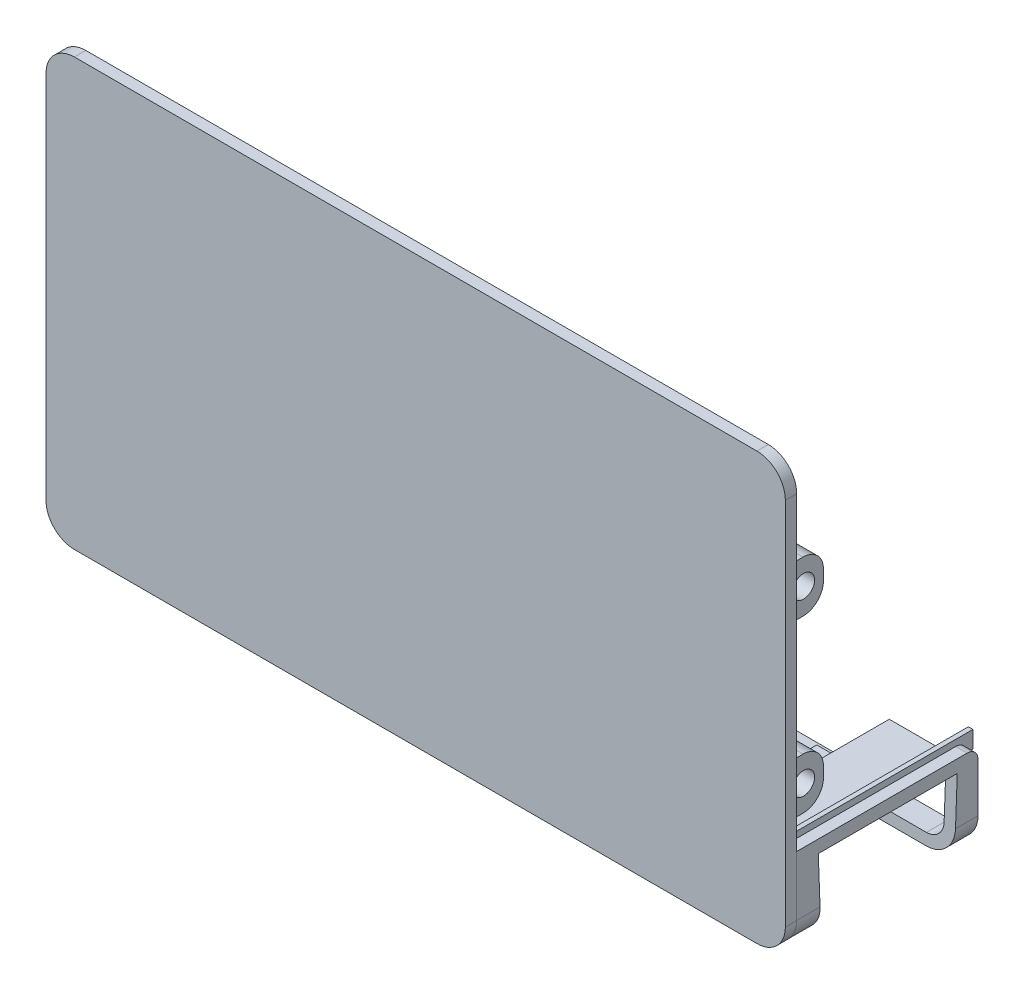
SolidWorks part; units mm, degrees
ref_plane "前视基准面" through (0, 0, 0) normal (0, 0, 1) x (1, 0, 0)
ref_plane "上视基准面" through (0, 0, 0) normal (0, 1, 0) x (1, 0, 0)
ref_plane "右视基准面" through (0, 0, 0) normal (1, 0, 0) x (0, 0, -1)
other "Configuration Table"
sketch "草图25" plane through (0, 0, 0) normal (0, 0, 1) x (1, 0, 0)
  line L0 (-60, -37.5) -> (60, -37.5)
  line L1 (65, -32.5) -> (65, 32.5)
  line L2 (60, 37.5) -> (-60, 37.5)
  line L3 (-65, 32.5) -> (-65, -32.5)
  arc A0 (60, -37.5) -> (65, -32.5) centre (60, -32.5) ccw
  arc A1 (65, 32.5) -> (60, 37.5) centre (60, 32.5) ccw
  arc A2 (-60, 37.5) -> (-65, 32.5) centre (-60, 32.5) ccw
  arc A3 (-65, -32.5) -> (-60, -37.5) centre (-60, -32.5) ccw
extrude "Flat_bottom_cover_T2" add sketch "草图25" along normal blind 2
sketch "草图26" plane through (0, 0, 0) normal (0, 0, 1) x (1, 0, 0)
  line L0 (-62.7, -19) -> (-56.3, -19)
  line L1 (-56.3, -19) -> (-56.3, -10)
  line L2 (-56.3, -10) -> (-62.7, -10)
  line L3 (-62.7, -10) -> (-62.7, -19)
  line L4 (-62.7, 11) -> (-56.3, 11)
  line L5 (-56.3, 11) -> (-56.3, 20)
  line L6 (-56.3, 20) -> (-62.7, 20)
  line L7 (-62.7, 20) -> (-62.7, 11)
extrude "Side_lock_ears_-1" add sketch "草图26" against normal blind 7
sketch "草图27" plane through (0, 0, 0) normal (0, 0, 1) x (1, 0, 0)
  line L0 (56.3, -19) -> (62.7, -19)
  line L1 (62.7, -19) -> (62.7, -10)
  line L2 (62.7, -10) -> (56.3, -10)
  line L3 (56.3, -10) -> (56.3, -19)
  line L4 (56.3, 11) -> (62.7, 11)
  line L5 (62.7, 11) -> (62.7, 20)
  line L6 (62.7, 20) -> (56.3, 20)
  line L7 (56.3, 20) -> (56.3, 11)
extrude "Side_lock_ears_1" add sketch "草图27" against normal blind 7
sketch "草图28" plane through (-62.7, 0, 0) normal (-1, 0, 0) x (0, 0, 1)
  circle A0 centre (-3.5, -14.5) radius 1.45
  circle A1 centre (-3.5, 15.5) radius 1.45
extrude "Screw_tip_relief_D2.9_-1" cut sketch "草图28" against normal blind 5.6
sketch "草图29" plane through (-62.7, 0, 0) normal (-1, 0, 0) x (0, 0, 1)
  circle A0 centre (-3.5, -14.5) radius 1.95
  circle A1 centre (-3.5, 15.5) radius 1.95
extrude "M2.5_heatset_D3.9_depth3.5_-1" cut sketch "草图29" against normal blind 3.5
sketch "草图30" plane through (62.7, 0, 0) normal (1, 0, 0) x (0, 0, -1)
  circle A0 centre (3.5, -14.5) radius 1.45
  circle A1 centre (3.5, 15.5) radius 1.45
extrude "Screw_tip_relief_D2.9_1" cut sketch "草图30" against normal blind 5.6
sketch "草图31" plane through (62.7, 0, 0) normal (1, 0, 0) x (0, 0, -1)
  circle A0 centre (3.5, -14.5) radius 1.95
  circle A1 centre (3.5, 15.5) radius 1.95
extrude "M2.5_heatset_D3.9_depth3.5_1" cut sketch "草图31" against normal blind 3.5
fillet "圆角1" radius 3.6 8 edges at (-59.5, -19, -7) (-59.5, -10, -7) (-59.5, 20, -7) (-59.5, 11, -7) (59.5, 20, -7) (59.5, 11, -7) (59.5, -10, -7) (59.5, -19, -7)
sketch "草图34" plane through (0, 0, 0) normal (0, 0, -1) x (-1, 0, 0)
  line L0 (59.9, -37.5) -> (59.9, -35.5)
  line L1 (60, -37.5) -> (-60, -37.5) construction
  line L2 (60, -35.5) -> (60, -38.0414) construction
  line L3 (-64.9748, -21.9) -> (-70.1323, -21.9) construction
  line L4 (-64.9748, -22) -> (-62.9748, -22)
  line L5 (-62.9748, -22) -> (-62.9748, -32.5)
  line L7 (-64.9748, -22) -> (-64.9748, -32.5)
  line L8 (-59.9748, -35.5) -> (59.9, -35.5)
  line L9 (59.9, -37.5) -> (-59.9748, -37.5)
  arc A0 (-62.9748, -32.5) -> (-59.9748, -35.5) centre (-59.9748, -32.5) ccw
  arc A1 (-64.9748, -32.5) -> (-59.9748, -37.5) centre (-59.9748, -32.5) ccw
  dimension "D1" = 2
  dimension "D2" = 0.1
  dimension "D4" = 0.1
  dimension "D3" = 2
extrude "凸台-拉伸2" add sketch "草图34" along normal blind 31.9
fillet "圆角2" radius 1.9 2 edges at (-59.9, -36.5, -31.9) (63.9748, -22, -31.9)
sketch "草图35" plane through (64.9748, 0, 0) normal (1, 0, 0) x (0, 0, -1)
  line L1 (28.2533, -24.2301) -> (3.8188, -24.2301)
  line L2 (28.2533, -24.2301) -> (27.6089, -41.4145)
  line L3 (27.6089, -41.4145) -> (4.4609, -41.4145)
  line L4 (3.8188, -24.2301) -> (4.4609, -41.4145)
extrude "切除-拉伸1" cut sketch "草图35" against normal blind 17
sketch "草图36" plane through (0, 0, 0) normal (0, 0, -1) x (-1, 0, 0)
  line L0 (-64.9748, -22) -> (-62.9748, -22) construction
  line L1 (-62.9748, -22) -> (-52.9748, -22)
  line L2 (-62.9748, -22) -> (-62.9748, -24.2301)
  line L3 (-62.9748, -24.2301) -> (-52.9748, -24.2301)
  line L4 (-52.9748, -22) -> (-52.9748, -24.2301)
  line L5 (-62.9748, -24.2301) -> (-64.9748, -24.2301) construction
  line L6 (58, -35.5) -> (-59.9748, -35.5) construction
  line L7 (-47.9725, -32.2834) -> (-40.2423, -32.2834)
  line L8 (-47.9725, -32.2834) -> (-47.9725, -35.5)
  line L9 (-47.9725, -35.5) -> (-40.2423, -35.5)
  line L10 (-40.2423, -32.2834) -> (-40.2423, -35.5)
  dimension "D1" = 10
extrude "凸台-拉伸3" add sketch "草图36" along normal blind 28.3
sketch "草图38" plane through (0, -32.2834, 0) normal (0, 1, 0) x (1, 0, 0)
  circle A0 centre (45.1498, 23.9901) radius 2
  circle A1 centre (45.165, 7.9909) radius 2
  dimension "D1" = 4
extrude "切除-拉伸2" cut sketch "草图38" against normal blind 3.4
sketch "草图39" plane through (0, 0, 0) normal (0, 0, -1) x (-1, 0, 0)
  line L0 (62.9, -32.5) -> (62.1, -32.5)
  line L1 (60, -35.4) -> (59.9, -35.4)
  line L2 (59.9, -35.4) -> (59.9, -35.5)
  line L3 (60, -34.6) -> (58, -34.6)
  line L4 (58, -34.6) -> (58, -35.5)
  line L5 (58, -37.5) -> (58, -35.5) construction
  line L6 (58, -35.5) -> (59.9, -35.5)
  line L7 (-62.9748, -23.9) -> (-64.9748, -23.9) construction
  line L8 (-62.9748, -23.9) -> (-62.1748, -23.9)
  line L9 (-62.9748, -23.9) -> (-62.9748, -20.9)
  line L10 (-62.9748, -20.9) -> (-62.1748, -20.9)
  line L11 (-62.1748, -23.9) -> (-62.1748, -20.9)
  line L12 (59.9, -35.5) -> (-40.2423, -35.5) construction
  arc A1 (60, -34.6) -> (62.1, -32.5) centre (60, -32.5) ccw
  arc A2 (60, -35.4) -> (62.9, -32.5) centre (60, -32.5) ccw
  arc A3 (60, -35.4) -> (62.9, -32.5) centre (60, -32.5) ccw
  dimension "D3" = 0.8
  dimension "D4" = 3
  dimension "D1" = 2.1
  dimension "D2" = 0.8
extrude "凸台-拉伸4" add sketch "草图39" along normal blind 33
sketch "草图40" plane through (0, -37.5, 0) normal (0, -1, 0) x (1, 0, 0)
  line L0 (59.9748, -31.9) -> (-58, -31.9) construction
  line L1 (64.9748, -31.9) -> (64.9748, -27.9432) construction
  circle A0 centre (21.9748, -27.4) radius 1
  circle A1 centre (17.9748, -27.4) radius 1
  circle A2 centre (13.9748, -27.4) radius 1
  circle A3 centre (9.9748, -27.4) radius 1
  circle A4 centre (5.9748, -27.4) radius 1
  circle A5 centre (1.9748, -27.4) radius 1
  circle A6 centre (-2.0252, -27.4) radius 1
  circle A7 centre (-6.0252, -27.4) radius 1
  circle A8 centre (-10.0252, -27.4) radius 1
  circle A9 centre (-14.0252, -27.4) radius 1
  circle A10 centre (-18.0252, -27.4) radius 1
  circle A11 centre (-22.0252, -27.4) radius 1
  circle A12 centre (-26.0252, -27.4) radius 1
  circle A13 centre (-30.0252, -27.4) radius 1
  circle A14 centre (-34.0252, -27.4) radius 1
  circle A15 centre (-38.0252, -27.4) radius 1
  circle A16 centre (-42.0252, -27.4) radius 1
  circle A17 centre (-46.0252, -27.4) radius 1
  circle A18 centre (-50.0252, -27.4) radius 1
  circle A19 centre (-54.0252, -27.4) radius 1
  circle A20 centre (17.9748, -23.4) radius 1
  circle A21 centre (13.9748, -23.4) radius 1
  circle A22 centre (9.9748, -23.4) radius 1
  circle A23 centre (5.9748, -23.4) radius 1
  circle A24 centre (1.9748, -23.4) radius 1
  circle A25 centre (-2.0252, -23.4) radius 1
  circle A26 centre (-6.0252, -23.4) radius 1
  circle A27 centre (-10.0252, -23.4) radius 1
  circle A28 centre (-14.0252, -23.4) radius 1
  circle A29 centre (-18.0252, -23.4) radius 1
  circle A30 centre (-22.0252, -23.4) radius 1
  circle A31 centre (-26.0252, -23.4) radius 1
  circle A32 centre (-30.0252, -23.4) radius 1
  circle A33 centre (-34.0252, -23.4) radius 1
  circle A34 centre (-38.0252, -23.4) radius 1
  circle A35 centre (-42.0252, -23.4) radius 1
  circle A36 centre (-46.0252, -23.4) radius 1
  circle A37 centre (-50.0252, -23.4) radius 1
  circle A38 centre (-54.0252, -23.4) radius 1
  circle A39 centre (17.9748, -19.4) radius 1
  circle A40 centre (13.9748, -19.4) radius 1
  circle A41 centre (9.9748, -19.4) radius 1
  circle A42 centre (5.9748, -19.4) radius 1
  circle A43 centre (1.9748, -19.4) radius 1
  circle A44 centre (-2.0252, -19.4) radius 1
  circle A45 centre (-6.0252, -19.4) radius 1
  circle A46 centre (-10.0252, -19.4) radius 1
  circle A47 centre (-14.0252, -19.4) radius 1
  circle A48 centre (-18.0252, -19.4) radius 1
  circle A49 centre (-22.0252, -19.4) radius 1
  circle A50 centre (-26.0252, -19.4) radius 1
  circle A51 centre (-30.0252, -19.4) radius 1
  circle A52 centre (-34.0252, -19.4) radius 1
  circle A53 centre (-38.0252, -19.4) radius 1
  circle A54 centre (-42.0252, -19.4) radius 1
  circle A55 centre (-46.0252, -19.4) radius 1
  circle A56 centre (-50.0252, -19.4) radius 1
  circle A57 centre (-54.0252, -19.4) radius 1
  circle A58 centre (17.9748, -15.4) radius 1
  circle A59 centre (13.9748, -15.4) radius 1
  circle A60 centre (9.9748, -15.4) radius 1
  circle A61 centre (5.9748, -15.4) radius 1
  circle A62 centre (1.9748, -15.4) radius 1
  circle A63 centre (-2.0252, -15.4) radius 1
  circle A64 centre (-6.0252, -15.4) radius 1
  circle A65 centre (-10.0252, -15.4) radius 1
  circle A66 centre (-14.0252, -15.4) radius 1
  circle A67 centre (-18.0252, -15.4) radius 1
  circle A68 centre (-22.0252, -15.4) radius 1
  circle A69 centre (-26.0252, -15.4) radius 1
  circle A70 centre (-30.0252, -15.4) radius 1
  circle A71 centre (-34.0252, -15.4) radius 1
  circle A72 centre (-38.0252, -15.4) radius 1
  circle A73 centre (-42.0252, -15.4) radius 1
  circle A74 centre (-46.0252, -15.4) radius 1
  circle A75 centre (-50.0252, -15.4) radius 1
  circle A76 centre (-54.0252, -15.4) radius 1
  circle A77 centre (17.9748, -11.4) radius 1
  circle A78 centre (13.9748, -11.4) radius 1
  circle A79 centre (9.9748, -11.4) radius 1
  circle A80 centre (5.9748, -11.4) radius 1
  circle A81 centre (1.9748, -11.4) radius 1
  circle A82 centre (-2.0252, -11.4) radius 1
  circle A83 centre (-6.0252, -11.4) radius 1
  circle A84 centre (-10.0252, -11.4) radius 1
  circle A85 centre (-14.0252, -11.4) radius 1
  circle A86 centre (-18.0252, -11.4) radius 1
  circle A87 centre (-22.0252, -11.4) radius 1
  circle A88 centre (-26.0252, -11.4) radius 1
  circle A89 centre (-30.0252, -11.4) radius 1
  circle A90 centre (-34.0252, -11.4) radius 1
  circle A91 centre (-38.0252, -11.4) radius 1
  circle A92 centre (-42.0252, -11.4) radius 1
  circle A93 centre (-46.0252, -11.4) radius 1
  circle A94 centre (-50.0252, -11.4) radius 1
  circle A95 centre (-54.0252, -11.4) radius 1
  circle A96 centre (21.9748, -23.4) radius 1
  circle A97 centre (21.9748, -19.4) radius 1
  circle A98 centre (21.9748, -15.4) radius 1
  circle A99 centre (21.9748, -11.4) radius 1
  dimension "D1" = 2
  dimension "D2" = 4.5
  dimension "D3" = 43
  dimension "D4" = 20
  dimension "D5" = 5
extrude "切除-拉伸3" cut sketch "草图40" against normal up to next (2 mm away)
ref_plane "基准面1" through (16.4748, 0, 0) normal (1, 0, 0) x (0, 0, -1)
sketch "草图41" plane through (16.4748, 0, 0) normal (1, 0, 0) x (0, 0, -1)
  line L0 (26.446, -35.5) -> (37.162, -30.0994)
  line L1 (4.2399, -35.5) -> (27.8307, -35.5) construction
  line L2 (37.162, -30.0994) -> (38.2667, -32.2914)
  line L3 (38.2667, -32.2914) -> (31.9, -35.5)
  line L4 (31.9, -35.5) -> (27.8307, -35.5) construction
  line L5 (31.9, -37.5) -> (31.9, -32.5) construction
  line L6 (26.446, -35.5) -> (31.9, -35.5)
  dimension "D1" = 12
extrude "凸台-拉伸5" add sketch "草图41" along normal blind 1.5
sketch "草图42" plane through (0, -35.5, 0) normal (0, 1, 0) x (1, 0, 0)
  line L0 (17.9748, 37.162) -> (17.9748, 26.446) construction
  line L1 (16.4748, 31.9) -> (17.9748, 31.9)
  line L2 (16.4748, 31.9) -> (16.4748, 0)
  line L3 (16.4748, 0) -> (17.9748, 0)
  line L4 (17.9748, 31.9) -> (17.9748, 0)
  line L5 (60, 0) -> (-60, 0) construction
  line L6 (-58, 31.9) -> (16.4748, 31.9) construction
  line L7 (-16.8, 31.9) -> (-15.3, 31.9)
  line L8 (-16.8, 31.9) -> (-16.8, 0)
  line L9 (-16.8, 0) -> (-15.3, 0)
  line L10 (-15.3, 31.9) -> (-15.3, 0)
  line L11 (-44.8, 31.9) -> (-43.3, 31.9)
  line L12 (-44.8, 31.9) -> (-44.8, 0)
  line L13 (-44.8, 0) -> (-43.3, 0)
  line L14 (-43.3, 31.9) -> (-43.3, 0)
  line L15 (-59.9, 33) -> (-59.9, 0) construction
  line L16 (16.4748, 37.162) -> (16.4748, 26.446) construction
  dimension "D1" = 1.5
  dimension "D2" = 15.1
  dimension "D3" = 43.1
extrude "凸台-拉伸6" add sketch "草图42" along normal blind 1.5
chamfer "倒角1" distance 1.5 angle 45 2 edges at (-16.05, -34, -31.9) (-44.05, -34, -31.9)
sketch "草图43" plane through (0, -37.5, 0) normal (0, -1, 0) x (1, 0, 0)
  line L1 (22.9748, -9.3) -> (-7.0252, -9.3)
  line L2 (22.9748, -9.3) -> (22.9748, 1.2)
  line L3 (22.9748, 1.2) -> (-7.0252, 1.2)
  line L4 (-7.0252, -9.3) -> (-7.0252, 1.2)
  line L5 (64.9748, -28.2533) -> (64.9748, -3.8188) construction
  line L7 (-60, 2) -> (60, 2) construction
  dimension "D1" = 10.5
  dimension "D2" = 30
  dimension "D3" = 42
  dimension "D4" = 0.8
extrude "切除-拉伸4" cut sketch "草图43" against normal blind 30
